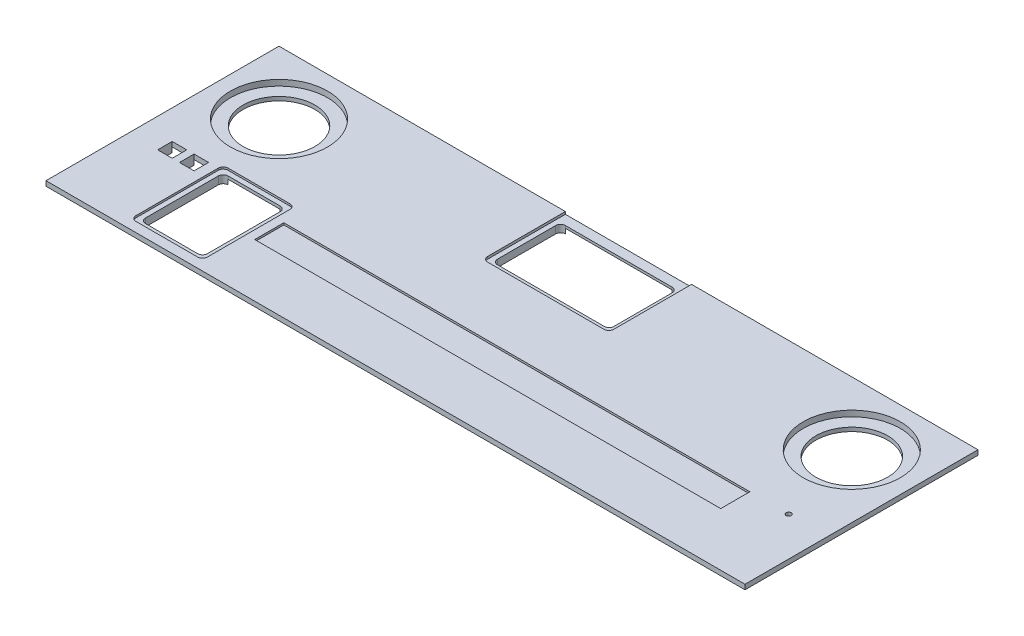
SolidWorks part; units mm, degrees
ref_plane "Front Plane" through (0, 0, 0) normal (0, 0, 1) x (1, 0, 0)
ref_plane "Top Plane" through (0, 0, 0) normal (0, 1, 0) x (1, 0, 0)
ref_plane "Right Plane" through (0, 0, 0) normal (1, 0, 0) x (0, 0, -1)
sketch "Sketch1" plane through (0, 0, 0) normal (0, 1, 0) x (1, 0, 0)
  line L1 (0, 0) -> (914.4, 0)
  line L2 (0, 0) -> (0, 304.8)
  line L3 (0, 304.8) -> (914.4, 304.8)
  line L4 (914.4, 0) -> (914.4, 304.8)
  dimension "D1" = 914.4
  dimension "D2" = 304.8
extrude "Boss-Extrude1" add sketch "Sketch1" along normal blind 12.7
sketch "Sketch3" plane through (0, 12.7, 0) normal (0, 1, 0) x (1, 0, 0)
  line L0 (933.9863, 107.95) -> (-7.7411, 107.95) construction
  line L1 (914.4, 0) -> (914.4, 304.8) construction
  line L2 (0, 304.8) -> (0, 0) construction
  line L3 (457.2, 304.8) -> (457.2, 0) construction
  line L4 (914.4, 304.8) -> (0, 304.8) construction
  line L5 (0, 0) -> (914.4, 0) construction
  line L6 (863.6, 304.8) -> (863.6, 0) construction
  line L8 (812.8, 96.2431) -> (812.8, 19.5383) construction
  line L9 (203.2, 151.0641) -> (203.2, 89.7006) construction
  line L10 (104.775, 133.35) -> (185.7375, 133.35)
  line L11 (203.2, 107.95) -> (812.8, 107.95)
  line L12 (203.2, 107.95) -> (203.2, 69.85)
  line L13 (203.2, 69.85) -> (812.8, 69.85)
  line L14 (812.8, 107.95) -> (812.8, 69.85)
  line L15 (38.1, 127) -> (57.15, 127)
  line L16 (38.1, 127) -> (38.1, 107.95)
  line L17 (38.1, 107.95) -> (57.15, 107.95)
  line L18 (57.15, 127) -> (57.15, 107.95)
  line L19 (66.675, 127) -> (85.725, 127)
  line L20 (66.675, 127) -> (66.675, 107.95)
  line L21 (66.675, 107.95) -> (85.725, 107.95)
  line L22 (85.725, 127) -> (85.725, 107.95)
  line L23 (98.425, 127) -> (98.425, 19.05)
  line L24 (381, 304.8) -> (533.4, 304.8) construction
  line L25 (381, 304.8) -> (381, 203.2) construction
  line L26 (381, 203.2) -> (533.4, 203.2) construction
  line L27 (533.4, 304.8) -> (533.4, 203.2) construction
  line L28 (152.4, 130.2491) -> (152.4, 0) construction
  line L29 (104.775, 12.7) -> (185.7375, 12.7)
  line L30 (192.0875, 127) -> (192.0875, 19.05)
  line L31 (169.2288, 116.8772) -> (169.2288, 116.6664)
  circle A0 centre (863.6, 107.95) radius 19.05
  circle A1 centre (152.4, 107.95) radius 19.05
  arc A2 (98.425, 19.05) -> (104.775, 12.7) centre (104.775, 19.05) ccw
  arc A3 (185.7375, 12.7) -> (192.0875, 19.05) centre (185.7375, 19.05) ccw
  arc A4 (185.7375, 133.35) -> (192.0875, 127) centre (185.7375, 127) cw
  arc A5 (104.775, 133.35) -> (98.425, 127) centre (104.775, 127) ccw
  circle A6 centre (82.55, 222.25) radius 63.5 construction
  circle A7 centre (831.85, 222.25) radius 63.5 construction
  circle A8 centre (111.125, 31.75) radius 6.35
  circle A9 centre (111.125, 63.5) radius 6.35
  circle A10 centre (142.875, 31.75) radius 6.35
  circle A11 centre (174.625, 31.75) radius 6.35
  point P54 (457.2, 203.2)
  point P61 (192.0875, 133.35)
  point P64 (98.425, 133.35)
  dimension "D6" = 12.7
  dimension "D7" = 38.1
  dimension "D16" = 6.35
  dimension "D18" = 127
  dimension "D19" = 107.95
  dimension "D22" = 127
  dimension "D28" = 38.1
  dimension "D29" = 12.7
  dimension "D30" = 12.7
  dimension "D31" = 12.7
  dimension "D32" = 12.7
  dimension "D1" = 50.8
  dimension "D2" = 50.8
  dimension "D3" = 609.6
  dimension "D4" = 93.6625
  dimension "D5" = 38.1
  dimension "D8" = 19.05
  dimension "D9" = 19.05
  dimension "D10" = 19.05
  dimension "D11" = 19.05
  dimension "D12" = 38.1
  dimension "D13" = 9.525
  dimension "D14" = 6.35
  dimension "D15" = 12.7
  dimension "D20" = 82.55
  dimension "D21" = 82.55
  dimension "D23" = 82.55
  dimension "D24" = 82.55
  dimension "D25" = 101.6
  dimension "D26" = 152.4
  dimension "D27" = 127
  dimension "D17" = 152.4
  dimension "D33" = 19.05
  dimension "D34" = 76.2
  dimension "D35" = 19.05
  dimension "D36" = 44.45
  dimension "D37" = 19.05
  dimension "D38" = 12.7
  dimension "D39" = 12.7
  dimension "D40" = 50.8
sketch "Sketch4" plane through (0, 12.7, 0) normal (0, 1, 0) x (1, 0, 0)
  line L0 (0, 304.8) -> (0, 127)
  line L1 (12.7, 292.1) -> (317.5, 292.1)
  line L2 (12.7, 292.1) -> (12.7, 139.7)
  line L3 (12.7, 139.7) -> (311.15, 139.7)
  line L4 (317.5, 292.1) -> (317.5, 146.05)
  line L5 (596.9, 292.1) -> (901.7, 292.1)
  line L6 (596.9, 292.1) -> (596.9, 146.05)
  line L7 (603.25, 139.7) -> (901.7, 139.7)
  line L8 (901.7, 292.1) -> (901.7, 139.7)
  line L9 (0, 127) -> (323.85, 127)
  line L10 (330.2, 304.8) -> (330.2, 133.35)
  line L11 (0, 304.8) -> (330.2, 304.8)
  line L12 (584.2, 304.8) -> (584.2, 133.35)
  line L13 (590.55, 127) -> (914.4, 127)
  line L14 (914.4, 304.8) -> (914.4, 127)
  line L15 (584.2, 304.8) -> (914.4, 304.8)
  line L16 (0, 304.8) -> (0, 0) construction
  line L17 (914.4, 304.8) -> (0, 304.8) construction
  line L18 (914.4, 0) -> (914.4, 304.8) construction
  line L19 (0, 127) -> (330.2, 127) construction
  line L20 (330.2, 304.8) -> (330.2, 127) construction
  line L21 (12.7, 139.7) -> (317.5, 139.7) construction
  line L22 (317.5, 292.1) -> (317.5, 139.7) construction
  line L23 (584.2, 304.8) -> (584.2, 127) construction
  line L24 (584.2, 127) -> (914.4, 127) construction
  line L25 (596.9, 292.1) -> (596.9, 139.7) construction
  line L26 (596.9, 139.7) -> (901.7, 139.7) construction
  arc A0 (323.85, 127) -> (330.2, 133.35) centre (323.85, 133.35) ccw
  arc A1 (311.15, 139.7) -> (317.5, 146.05) centre (311.15, 146.05) ccw
  arc A2 (584.2, 133.35) -> (590.55, 127) centre (590.55, 133.35) ccw
  arc A3 (596.9, 146.05) -> (603.25, 139.7) centre (603.25, 146.05) ccw
  point P34 (596.9, 139.7)
  dimension "D6" = 6.35
  dimension "D1" = 304.8
  dimension "D2" = 152.4
  dimension "D3" = 304.8
  dimension "D4" = 152.4
  dimension "D5" = 12.7
sketch "Sketch5" plane through (0, 12.7, 0) normal (0, 1, 0) x (1, 0, 0)
  line L0 (203.2, 107.95) -> (203.2, 69.85) construction
  line L1 (203.2, 107.95) -> (203.2, 69.85)
  line L2 (203.2, 69.85) -> (812.8, 69.85) construction
  line L3 (203.2, 69.85) -> (812.8, 69.85)
  line L12 (812.8, 107.95) -> (812.8, 69.85) construction
  line L13 (203.2, 107.95) -> (812.8, 107.95) construction
  line L14 (812.8, 107.95) -> (812.8, 69.85)
  line L15 (203.2, 107.95) -> (812.8, 107.95)
extrude "Cut-Extrude3" cut sketch "Sketch5" against normal blind 2.54
sketch "Sketch6" plane through (0, 12.7, 0) normal (0, 1, 0) x (1, 0, 0)
  circle A0 centre (82.55, 222.25) radius 46.99
  circle A1 centre (831.85, 222.25) radius 46.99
  dimension "D1" = 93.98
  dimension "D2" = 93.98
extrude "Cut-Extrude4" cut sketch "Sketch6" against normal through all
sketch "Sketch7" plane through (0, 12.7, 0) normal (0, 1, 0) x (1, 0, 0)
  circle A0 centre (82.55, 222.25) radius 63.5 construction
  circle A1 centre (82.55, 222.25) radius 63.5
  circle A2 centre (831.85, 222.25) radius 63.5 construction
  circle A3 centre (831.85, 222.25) radius 63.5
extrude "Cut-Extrude5" cut sketch "Sketch7" against normal blind 7.62
sketch "Sketch8" plane through (0, 12.7, 0) normal (0, 1, 0) x (1, 0, 0)
  line L0 (381, 304.8) -> (381, 203.2) construction
  line L1 (381, 203.2) -> (533.4, 203.2) construction
  line L2 (533.4, 304.8) -> (533.4, 203.2) construction
  line L4 (381, 285.75) -> (381, 209.55)
  line L5 (387.35, 203.2) -> (527.05, 203.2)
  line L6 (533.4, 285.75) -> (533.4, 209.55)
  line L7 (527.05, 292.1) -> (387.35, 292.1)
  line L8 (914.4, 304.8) -> (0, 304.8) construction
  arc A0 (527.05, 292.1) -> (533.4, 285.75) centre (527.05, 285.75) cw
  arc A1 (527.05, 203.2) -> (533.4, 209.55) centre (527.05, 209.55) ccw
  arc A2 (381, 209.55) -> (387.35, 203.2) centre (387.35, 209.55) ccw
  arc A3 (387.35, 292.1) -> (381, 285.75) centre (387.35, 285.75) ccw
  dimension "D2" = 6.35
  dimension "D1" = 12.7
extrude "Cut-Extrude6" cut sketch "Sketch8" against normal through all
sketch "Sketch9" plane through (0, 12.7, 0) normal (0, 1, 0) x (1, 0, 0)
  line L0 (914.4, 304.8) -> (0, 304.8) construction
  line L1 (539.75, 304.8) -> (374.65, 304.8)
  line L2 (539.75, 304.8) -> (539.75, 202.946)
  line L3 (533.4, 196.596) -> (381, 196.596)
  line L4 (374.65, 304.8) -> (374.65, 202.946)
  line L5 (381, 304.8) -> (381, 203.2) construction
  line L6 (381, 203.2) -> (533.4, 203.2) construction
  line L7 (457.2, 304.8) -> (457.2, 0) construction
  arc A0 (539.75, 202.946) -> (533.4, 196.596) centre (533.4, 202.946) cw
  arc A1 (381, 196.596) -> (374.65, 202.946) centre (381, 202.946) cw
  point P10 (457.2, 196.596)
  dimension "D3" = 6.35
  dimension "D1" = 6.35
  dimension "D2" = 6.604
extrude "Cut-Extrude7" cut sketch "Sketch9" against normal blind 3.175
sketch "Sketch13" plane through (0, 12.7, 0) normal (0, 1, 0) x (1, 0, 0)
  line L0 (57.15, 127) -> (57.15, 107.95) construction
  line L1 (38.1, 107.95) -> (57.15, 107.95)
  line L2 (38.1, 107.95) -> (38.1, 127)
  line L3 (38.1, 127) -> (57.15, 127)
  line L4 (57.15, 107.95) -> (57.15, 127)
  line L5 (85.725, 127) -> (85.725, 107.95) construction
  line L6 (66.675, 107.95) -> (85.725, 107.95)
  line L7 (66.675, 107.95) -> (66.675, 127)
  line L8 (66.675, 127) -> (85.725, 127)
  line L9 (85.725, 107.95) -> (85.725, 127)
  dimension "D1" = 19.05
  dimension "D2" = 19.05
  dimension "D3" = 19.05
extrude "Cut-Extrude11" cut sketch "Sketch13" against normal through all
sketch "Sketch14" plane through (0, 12.7, 0) normal (0, 1, 0) x (1, 0, 0)
  line L0 (38.1, 127) -> (38.1, 107.95) construction
  line L1 (38.1, 127) -> (57.15, 127) construction
  line L2 (57.15, 127) -> (57.15, 107.95) construction
  line L3 (38.1, 107.95) -> (57.15, 107.95) construction
  line L4 (66.675, 127) -> (66.675, 107.95) construction
  line L5 (66.675, 127) -> (85.725, 127) construction
  line L6 (85.725, 127) -> (85.725, 107.95) construction
  line L7 (66.675, 107.95) -> (85.725, 107.95) construction
  line L8 (38.1, 127) -> (38.1, 107.95)
  line L9 (38.1, 127) -> (57.15, 127)
  line L10 (57.15, 127) -> (57.15, 107.95)
  line L11 (38.1, 107.95) -> (57.15, 107.95)
  line L12 (66.675, 127) -> (66.675, 107.95)
  line L13 (66.675, 127) -> (85.725, 127)
  line L14 (85.725, 127) -> (85.725, 107.95)
  line L15 (66.675, 107.95) -> (85.725, 107.95)
extrude "Cut-Extrude12" [suppressed] cut sketch "Sketch14" against normal blind 5.08
sketch "Sketch21" plane through (0, 12.7, 0) normal (0, 1, 0) x (1, 0, 0)
  circle A0 centre (152.4, 107.95) radius 15.875
  dimension "D1" = 31.75
extrude "Cut-Extrude17" [suppressed] cut sketch "Sketch21" against normal through all
sketch "Sketch22" [suppressed] plane through (0, 12.7, 0) normal (0, 1, 0) x (1, 0, 0)
  circle A0 centre (152.4, 107.95) radius 22.225
  circle A1 centre (152.4, 107.95) radius 15.875 construction
  dimension "D1" = 6.35
extrude "Cut-Extrude18" [suppressed] cut sketch "Sketch22" against normal blind 2.54
sketch "Sketch24" plane through (0, 12.7, 0) normal (0, 1, 0) x (1, 0, 0)
  line L0 (104.775, 133.35) -> (185.7375, 133.35) construction
  line L1 (192.0875, 127) -> (192.0875, 19.05) construction
  line L2 (104.775, 12.7) -> (185.7375, 12.7) construction
  line L3 (98.425, 127) -> (98.425, 19.05) construction
  line L4 (104.775, 133.35) -> (185.7375, 133.35) construction
  line L5 (192.0875, 127) -> (192.0875, 19.05) construction
  line L6 (104.775, 12.7) -> (185.7375, 12.7) construction
  line L7 (98.425, 127) -> (98.425, 19.05) construction
  line L8 (111.125, 127) -> (179.3875, 127)
  line L9 (185.7375, 120.65) -> (185.7375, 25.4)
  line L10 (111.125, 19.05) -> (179.3875, 19.05)
  line L11 (104.775, 120.65) -> (104.775, 25.4)
  line L12 (104.775, 19.05) -> (185.7375, 19.05) construction
  line L13 (104.775, 127) -> (104.775, 19.05) construction
  line L14 (185.7375, 127) -> (185.7375, 19.05) construction
  line L15 (104.775, 127) -> (185.7375, 127) construction
  arc A0 (192.0875, 127) -> (185.7375, 133.35) centre (185.7375, 127) ccw construction
  arc A1 (185.7375, 12.7) -> (192.0875, 19.05) centre (185.7375, 19.05) ccw construction
  arc A2 (98.425, 19.05) -> (104.775, 12.7) centre (104.775, 19.05) ccw construction
  arc A3 (104.775, 133.35) -> (98.425, 127) centre (104.775, 127) ccw construction
  arc A4 (192.0875, 127) -> (185.7375, 133.35) centre (185.7375, 127) ccw construction
  arc A5 (185.7375, 12.7) -> (192.0875, 19.05) centre (185.7375, 19.05) ccw construction
  arc A6 (98.425, 19.05) -> (104.775, 12.7) centre (104.775, 19.05) ccw construction
  arc A7 (104.775, 133.35) -> (98.425, 127) centre (104.775, 127) ccw construction
  arc A8 (104.775, 120.65) -> (111.125, 127) centre (111.125, 120.65) cw
  arc A9 (179.3875, 127) -> (185.7375, 120.65) centre (179.3875, 120.65) cw
  arc A10 (179.3875, 19.05) -> (185.7375, 25.4) centre (179.3875, 25.4) ccw
  arc A12 (111.125, 19.05) -> (104.775, 25.4) centre (111.125, 25.4) cw
  arc A13 (104.775, 19.05) -> (104.775, 19.05) centre (104.775, 19.05) ccw construction
  arc A14 (185.7375, 19.05) -> (185.7375, 19.05) centre (185.7375, 19.05) ccw construction
  arc A15 (185.7375, 127) -> (185.7375, 127) centre (185.7375, 127) ccw construction
  arc A16 (104.775, 127) -> (104.775, 127) centre (104.775, 127) ccw construction
  dimension "D2" = 6.35
  dimension "D1" = 6.35
extrude "Cut-Extrude19" cut sketch "Sketch24" against normal through all
sketch "Sketch25" plane through (0, 12.7, 0) normal (0, 1, 0) x (1, 0, 0)
  line L0 (104.775, 133.35) -> (185.7375, 133.35) construction
  line L1 (192.0875, 127) -> (192.0875, 19.05) construction
  line L2 (104.775, 12.7) -> (185.7375, 12.7) construction
  line L3 (98.425, 127) -> (98.425, 19.05) construction
  line L4 (104.775, 133.35) -> (185.7375, 133.35)
  line L5 (192.0875, 127) -> (192.0875, 19.05)
  line L6 (104.775, 12.7) -> (185.7375, 12.7)
  line L7 (98.425, 127) -> (98.425, 19.05)
  arc A0 (192.0875, 127) -> (185.7375, 133.35) centre (185.7375, 127) ccw construction
  arc A1 (185.7375, 12.7) -> (192.0875, 19.05) centre (185.7375, 19.05) ccw construction
  arc A2 (98.425, 19.05) -> (104.775, 12.7) centre (104.775, 19.05) ccw construction
  arc A3 (104.775, 133.35) -> (98.425, 127) centre (104.775, 127) ccw construction
  arc A4 (192.0875, 127) -> (185.7375, 133.35) centre (185.7375, 127) ccw
  arc A5 (185.7375, 12.7) -> (192.0875, 19.05) centre (185.7375, 19.05) ccw
  arc A6 (98.425, 19.05) -> (104.775, 12.7) centre (104.775, 19.05) ccw
  arc A7 (104.775, 133.35) -> (98.425, 127) centre (104.775, 127) ccw
extrude "Cut-Extrude20" cut sketch "Sketch25" against normal blind 2.54
sketch "Sketch26" plane through (0, 12.7, 0) normal (0, 1, 0) x (1, 0, 0)
  circle A0 centre (863.6, 107.95) radius 3.302
  dimension "D1" = 6.604
extrude "Cut-Extrude21" cut sketch "Sketch26" against normal through all
sketch "Sketch19" plane through (0, 0, 0) normal (0, -1, 0) x (1, 0, 0)
  line L0 (0, -127) -> (323.85, -127) construction
  line L1 (0, 0) -> (914.4, 0)
  line L2 (0, 0) -> (0, -304.8)
  line L3 (0, -304.8) -> (914.4, -304.8)
  line L4 (914.4, 0) -> (914.4, -304.8)
  line L5 (596.9, -292.1) -> (596.9, -146.05) construction
  line L6 (12.7, -139.7) -> (12.7, -292.1)
  line L7 (12.7, -292.1) -> (317.5, -292.1)
  line L8 (603.25, -139.7) -> (901.7, -139.7) construction
  line L9 (590.55, -127) -> (914.4, -127) construction
  line L10 (330.2, -304.8) -> (330.2, -133.35) construction
  line L11 (596.9, -292.1) -> (901.7, -292.1)
  line L12 (901.7, -139.7) -> (901.7, -292.1)
  line L13 (317.5, -292.1) -> (317.5, -146.05) construction
  line L14 (12.7, -127) -> (12.7, -12.7)
  line L15 (12.7, -12.7) -> (901.7, -12.7)
  line L16 (901.7, -127) -> (901.7, -12.7)
  line L17 (584.2, -304.8) -> (584.2, -133.35) construction
  line L18 (12.7, -139.7) -> (311.15, -139.7) construction
  line L19 (596.9, -292.1) -> (596.9, -146.05)
  line L20 (330.2, -292.1) -> (584.2, -292.1)
  line L21 (603.25, -139.7) -> (901.7, -139.7)
  line L22 (590.55, -127) -> (901.7, -127)
  line L23 (584.2, -292.1) -> (584.2, -133.35)
  line L24 (330.2, -292.1) -> (330.2, -133.35)
  line L25 (317.5, -292.1) -> (317.5, -146.05)
  line L26 (12.7, -127) -> (323.85, -127)
  line L27 (12.7, -139.7) -> (311.15, -139.7)
  arc A0 (603.25, -139.7) -> (596.9, -146.05) centre (603.25, -146.05) ccw construction
  arc A1 (590.55, -127) -> (584.2, -133.35) centre (590.55, -133.35) ccw construction
  arc A2 (317.5, -146.05) -> (311.15, -139.7) centre (311.15, -146.05) ccw construction
  arc A3 (330.2, -133.35) -> (323.85, -127) centre (323.85, -133.35) ccw construction
  arc A4 (603.25, -139.7) -> (596.9, -146.05) centre (603.25, -146.05) ccw
  arc A5 (590.55, -127) -> (584.2, -133.35) centre (590.55, -133.35) ccw
  arc A6 (317.5, -146.05) -> (311.15, -139.7) centre (311.15, -146.05) ccw
  arc A7 (330.2, -133.35) -> (323.85, -127) centre (323.85, -133.35) ccw
  dimension "D1" = 12.7
extrude "Cut-Extrude16" cut sketch "Sketch19" against normal blind 6.35
sketch "Sketch23" plane through (0, 0, 0) normal (0, -1, 0) x (1, 0, 0)
  line L0 (847.9254, -12.7) -> (933.5678, -12.7)
  line L1 (12.7, -12.7) -> (901.7, -12.7) construction
  line L2 (901.7, -50.534) -> (901.7, 49.3195)
  line L3 (901.7, -127) -> (901.7, -12.7) construction
  line L5 (901.7, -12.7) -> (914.4, -12.7)
  line L6 (901.7, -12.7) -> (901.7, 0)
  line L7 (901.7, 0) -> (914.4, 0)
  line L8 (914.4, -12.7) -> (914.4, 0)
  dimension "D1" = 12.7
  dimension "D2" = 12.7
sketch "Sketch27" plane through (0, 12.7, 0) normal (0, 1, 0) x (1, 0, 0)
  line L0 (104.775, 133.35) -> (185.7375, 133.35) construction
  line L1 (192.0875, 127) -> (192.0875, 19.05) construction
  line L2 (104.775, 12.7) -> (185.7375, 12.7) construction
  line L3 (98.425, 127) -> (98.425, 19.05) construction
  line L4 (104.775, 133.35) -> (185.7375, 133.35)
  line L5 (192.0875, 127) -> (192.0875, 19.05)
  line L6 (104.775, 12.7) -> (185.7375, 12.7)
  line L7 (98.425, 127) -> (98.425, 19.05)
  line L8 (111.125, 127) -> (179.3875, 127) construction
  line L9 (111.125, 127) -> (179.3875, 127) construction
  line L10 (104.775, 25.4) -> (104.775, 120.65) construction
  line L11 (179.3875, 19.05) -> (111.125, 19.05) construction
  line L12 (185.7375, 120.65) -> (185.7375, 25.4) construction
  line L13 (104.775, 25.4) -> (104.775, 120.65) construction
  line L14 (179.3875, 19.05) -> (111.125, 19.05) construction
  line L15 (185.7375, 120.65) -> (185.7375, 25.4) construction
  line L16 (136.525, 129.0783) -> (136.525, 101.3305) construction
  line L18 (94.0016, 107.95) -> (212.4361, 107.95) construction
  line L19 (933.9863, 107.95) -> (-7.7411, 107.95) construction
  line L20 (203.2, 107.95) -> (812.8, 107.95) construction
  line L21 (136.525, 107.95) -> (116.6064, 119.45) construction
  line L22 (136.525, 107.95) -> (136.525, 80.2047) construction
  line L23 (136.525, 107.95) -> (156.4436, 119.45) construction
  line L24 (136.525, 107.95) -> (123.5346, 115.45) construction
  line L25 (136.525, 107.95) -> (149.5154, 115.45) construction
  line L26 (86.9826, 34.29) -> (208.5237, 34.29) construction
  line L27 (81.96, 70.3217) -> (211.1661, 70.3217) construction
  arc A0 (192.0875, 127) -> (185.7375, 133.35) centre (185.7375, 127) ccw construction
  arc A1 (185.7375, 12.7) -> (192.0875, 19.05) centre (185.7375, 19.05) ccw construction
  arc A2 (98.425, 19.05) -> (104.775, 12.7) centre (104.775, 19.05) ccw construction
  arc A3 (104.775, 133.35) -> (98.425, 127) centre (104.775, 127) ccw construction
  arc A4 (192.0875, 127) -> (185.7375, 133.35) centre (185.7375, 127) ccw
  arc A5 (185.7375, 12.7) -> (192.0875, 19.05) centre (185.7375, 19.05) ccw
  arc A6 (98.425, 19.05) -> (104.775, 12.7) centre (104.775, 19.05) ccw
  arc A7 (104.775, 133.35) -> (98.425, 127) centre (104.775, 127) ccw
  arc A8 (111.125, 127) -> (104.775, 120.65) centre (111.125, 120.65) ccw construction
  arc A9 (104.775, 25.4) -> (111.125, 19.05) centre (111.125, 25.4) ccw construction
  arc A10 (179.3875, 19.05) -> (185.7375, 25.4) centre (179.3875, 25.4) ccw construction
  arc A11 (185.7375, 120.65) -> (179.3875, 127) centre (179.3875, 120.65) ccw construction
  arc A12 (111.125, 127) -> (104.775, 120.65) centre (111.125, 120.65) ccw construction
  arc A13 (104.775, 25.4) -> (111.125, 19.05) centre (111.125, 25.4) ccw construction
  arc A14 (179.3875, 19.05) -> (185.7375, 25.4) centre (179.3875, 25.4) ccw construction
  arc A15 (185.7375, 120.65) -> (179.3875, 127) centre (179.3875, 120.65) ccw construction
  circle A16 centre (136.525, 107.95) radius 10.1
  circle A17 centre (136.525, 107.95) radius 23 construction
  circle A18 centre (136.525, 107.95) radius 15 construction
  circle A19 centre (123.5346, 115.45) radius 1.75
  circle A20 centre (149.5154, 115.45) radius 1.75
  circle A21 centre (136.525, 92.95) radius 1.75
  circle A22 centre (120.015, 34.29) radius 8.255 construction
  circle A23 centre (158.115, 34.29) radius 8.255 construction
  circle A24 centre (170.4975, 70.3217) radius 8.255 construction
  circle A25 centre (132.3975, 70.3217) radius 8.255 construction
  circle A26 centre (120.015, 34.29) radius 4.445
  circle A27 centre (158.115, 34.29) radius 4.445
  circle A28 centre (170.4975, 70.3217) radius 4.445
  circle A29 centre (132.3975, 70.3217) radius 4.445
  point P44 (136.525, 107.95)
  dimension "D1" = 20.2
  dimension "D2" = 46
  dimension "D5" = 30
  dimension "D6" = 3.5
  dimension "D11" = 16.51
  dimension "D13" = 16.51
  dimension "D15" = 16.51
  dimension "D17" = 16.51
  dimension "D19" = 8.89
  dimension "D20" = 8.89
  dimension "D21" = 8.89
  dimension "D22" = 8.89
  dimension "D3" = 38.1
  dimension "D8" = 120
  dimension "D9" = 15.24
  dimension "D10" = 38.1
  dimension "D12" = 15.24
  dimension "D14" = 38.1
  dimension "D16" = 15.24
  dimension "D18" = 38.1
  dimension "D4" = 3
  dimension "D7" = 3
equation "\"D2@Sketch12\" = \"D1@Sketch12\""
equation "\"D3@Sketch12\" = \"D1@Sketch12\""
equation "\"D4@Sketch12\" = \"D1@Sketch12\""
equation "\"D3@Sketch13\" = \"D1@Sketch13\""
equation "\"D6@Sketch15\" = \"D4@Sketch15\" / 2"
equation "\"D9@Sketch3\"=\"D8@Sketch3\""
equation "\"D13@Sketch27\"=\"D11@Sketch27\""
equation "\"D15@Sketch27\"=\"D11@Sketch27\""
equation "\"D17@Sketch27\"=\"D11@Sketch27\""
equation "\"D20@Sketch27\"=\"D19@Sketch27\""
equation "\"D21@Sketch27\"=\"D19@Sketch27\""
equation "\"D22@Sketch27\"=\"D19@Sketch27\""
